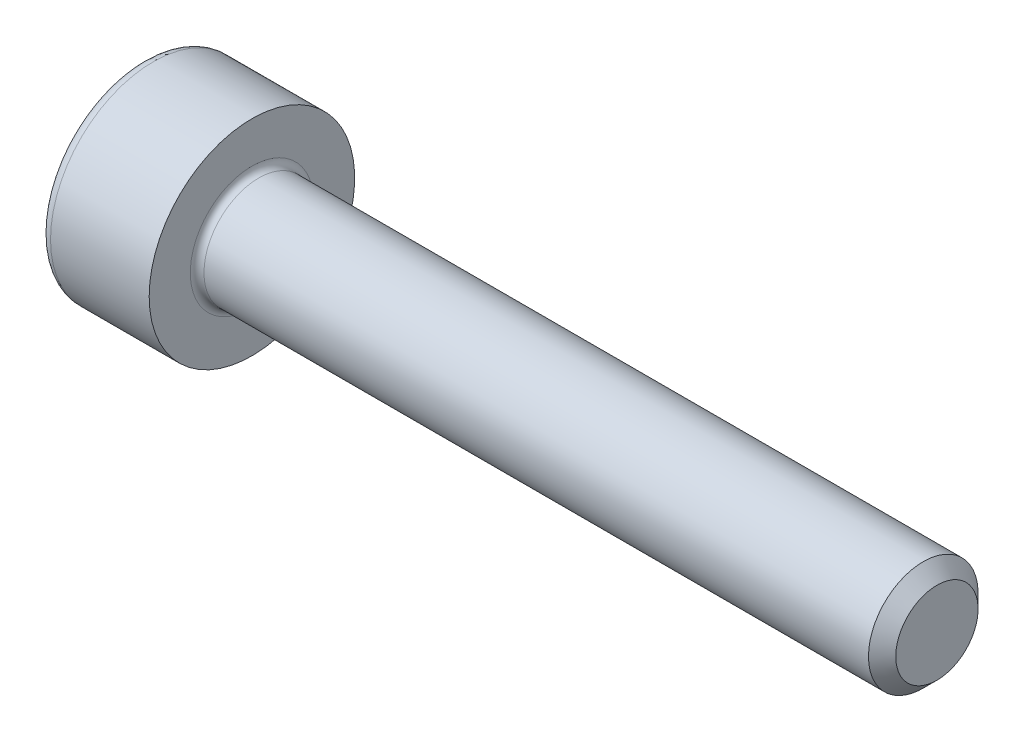
SolidWorks part; units mm, degrees
revolve "Base-Revolve" add sketch "BodySke"
sketch "BodySke" plane through (0, 0, 0) normal (0, 0, 1) x (1, 0, 0)
  line L0 (0, 0) -> (0, 1.5)
  line L1 (0, 1.5) -> (1.6, 1.5)
  line L2 (1.6, 1.5) -> (1.6, 0.8)
  line L3 (1.6, 0.8) -> (11.401, 0.8)
  line L4 (11.6, 0.601) -> (11.6, 0)
  line L5 (11.6, 0) -> (0, 0)
  line L6 (-31.75, 0) -> (127, 0) construction
  line L8 (11.6, 0.601) -> (11.401, 0.8)
  line L10 (11.6, -0.601) -> (11.401, -0.8) construction
  line L11 (1.95, 9.525) -> (1.95, 3.175) construction
  line L12 (1.6, 9.525) -> (1.6, 3.175) construction
  line L13 (-48.4, 9.525) -> (-48.4, 3.175) construction
  dimension "Head_ht" = 1.6
  dimension "Length" = 10
  dimension "Body_ch_ang" = 45
  dimension "Diameter" = 1.6
  dimension "Minor_dia" = 1.202
  dimension "Advance" = 0.35
  dimension "Thread_nom" = 10
  dimension "Thread_length" = 60
  dimension "Head_dia" = 3
cosmetic thread "ThreadCosmetic" [suppressed]
fillet "Fillet1" radius 0.1 1 edges at (1.6, 0, 0.8)
fillet "Fillet2" radius 0.16 1 edges at (0, 0, 1.5)
ref_plane "Plane1" through (0, 0, 0) normal (0, 0, 1) x (1, 0, 0)
ref_plane "Plane2" through (0, 0, 0) normal (0, 1, 0) x (1, 0, 0)
ref_plane "Plane3" through (0, 0, 0) normal (1, 0, 0) x (0, 0, -1)
sketch "Sketch2" plane through (0, 0, 0) normal (0, 0, 1) x (1, 0, 0)
  line L0 (0, 0.76) -> (0.7, 0.76)
  line L1 (0.7, 0.76) -> (1.1388, 0)
  line L2 (-31.75, 0) -> (127, 0) construction
  line L3 (1.1388, 0) -> (0, 0)
  line L4 (0, 0) -> (0, 0.76)
  line L6 (0, 0) -> (47.625, 0) construction
  dimension "D1" = 0.76
  dimension "D2" = 60
  dimension "Depth" = 0.7
revolve "Hex-PreBroach" cut sketch "Sketch2" angle 360 about L6
sketch "Sketch3" plane through (0, 0, 0) normal (-1, 0, 0) x (0, 0.5, 0.866)
  line L0 (0.4388, 0.76) -> (-0.4388, 0.76)
  line L1 (-0.4388, 0.76) -> (-0.8776, 0)
  line L2 (0.4388, 0.76) -> (0.8776, 0)
  line L3 (0.4388, -0.76) -> (0.8776, 0)
  line L4 (0.4388, -0.76) -> (-0.4388, -0.76)
  line L5 (-0.4388, -0.76) -> (-0.8776, 0)
  dimension "D1" = 0.76
  dimension "D2" = 0.76
  dimension "Hex_size" = 1.52
extrude "Hex" cut sketch "Sketch3" against normal blind 0.7
sketch "ThdSchSke" plane through (0, 0, 0) normal (0, 0, 1) x (1, 0, 0)
  line L0 (2.65, -0.601) -> (2.5107, -0.8)
  line L1 (2.65, -0.601) -> (2.7893, -0.8)
  line L2 (2.7893, -0.8) -> (2.7893, -1)
  line L3 (-3.175, 0) -> (5.1513, 0) construction
  line L4 (0, 1.34) -> (0, -1.34) construction
  line L5 (2.7893, -1) -> (2.5107, -1)
  line L6 (2.5107, -1) -> (2.5107, -0.8)
  dimension "Thread_minor" = 1.202
  dimension "Diameter" = 1.6
  dimension "Start" = 2.65
revolve "ThreadSchematic" [suppressed] cut sketch "ThdSchSke" angle 360 about L3
pattern_linear "ThdSchPat" [suppressed]
equation "\"D2@Sketch3\" = \"Hex_size@Sketch3\" / 2"
equation "\"D1@Sketch3\" = \"Hex_size@Sketch3\" / 2"
equation "\"D1@Sketch2\" = \"Hex_size@Sketch3\" / 2"
equation "\"Thread_minor@ThreadCosmetic\"  =  \"Minor_dia@BodySke\""
equation "\"Depth@Sketch2\" =  \"Key_eng@Hex\""
equation "\"Thread_length@ThreadCosmetic\" = ((sgn( (\"Length@BodySke\" - \"Advance@BodySke\" * 3.0) - \"Thread_nom@BodySke\" )-1)*( (\"Length@BodySke\" - \"Advance@BodySke\" * 3.0) - \"Thread_nom@BodySke\" ))/-2+ \"Thread_nom@BodySke\""
equation "\"Thread_minor@ThdSchSke\" = \"Minor_dia@BodySke\""
equation "\"Diameter@ThdSchSke\" = \"Diameter@BodySke\""
equation "\"Overcut@ThdSchSke\" = \"Diameter@BodySke\" * 1.25"
equation "\"Start@ThdSchSke\" = \"Head_ht@BodySke\" + \"Length@BodySke\" - \"Thread_length@ThreadCosmetic\"  '---Non-countersunk---"
equation "\"Num_threads@ThdSchPat\" = int( \"Thread_length@ThreadCosmetic\" / \"Advance@BodySke\" + 0.999 )  + 1"
equation "\"Advance@ThdSchPat\" = \"Thread_length@ThreadCosmetic\" /  (\"Num_threads@ThdSchPat\" - 1) 'relax it"
equation "\"Num_threads@ThdSchPat\" = \"Num_threads@ThdSchPat\" - sgn( \"Num_threads@ThdSchPat\" - 1) '---chamfered tips only---"
